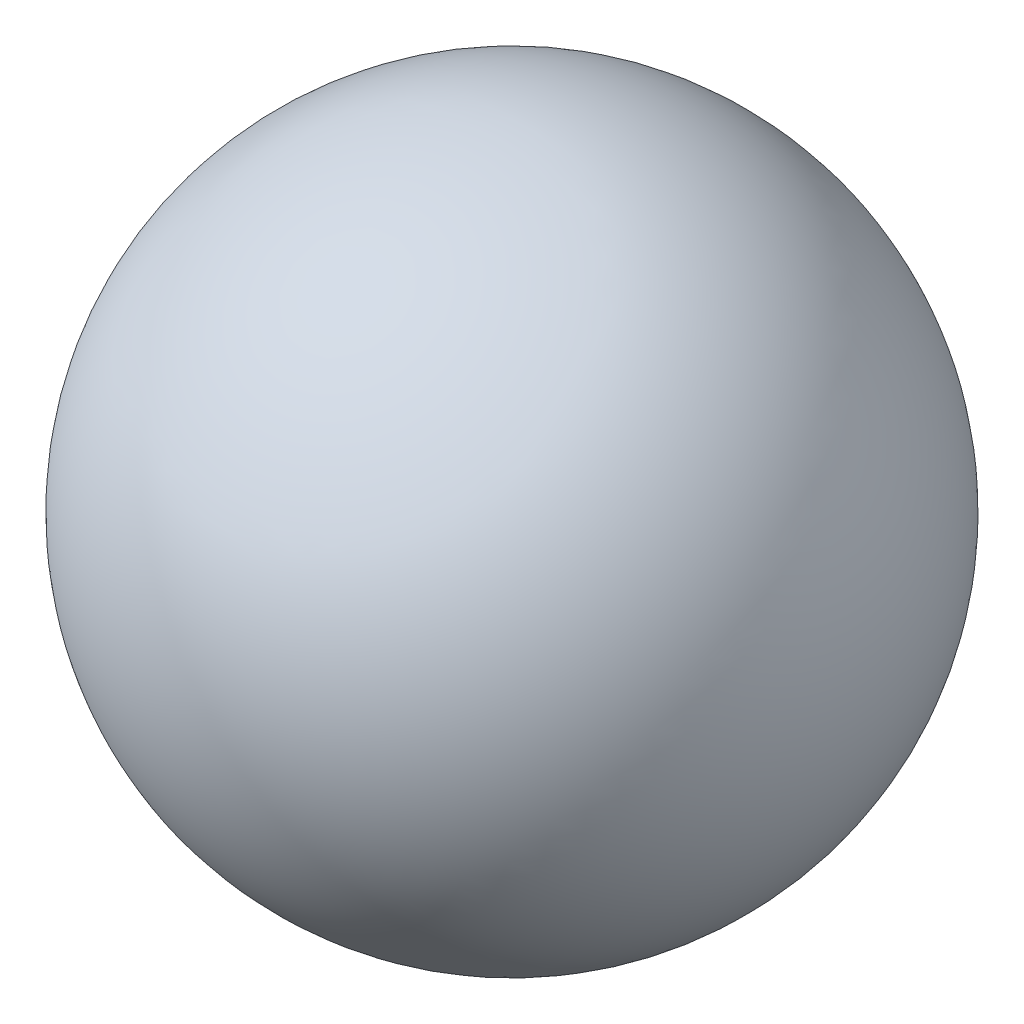
SolidWorks part; units mm, degrees
ref_plane "Front Plane" through (0, 0, 0) normal (0, 0, 1) x (1, 0, 0)
ref_plane "Top Plane" through (0, 0, 0) normal (0, 1, 0) x (1, 0, 0)
ref_plane "Right Plane" through (0, 0, 0) normal (1, 0, 0) x (0, 0, -1)
sketch "Sketch1" plane through (0, 0, 0) normal (0, 1, 0) x (1, 0, 0)
  line L0 (0, 15.24) -> (0, -15.24)
  arc A0 (0, -15.24) -> (0, 15.24) centre (0, 0) ccw
  dimension "D1" = 30.48
revolve "Revolve1" add sketch "Sketch1" angle 360 about L0
